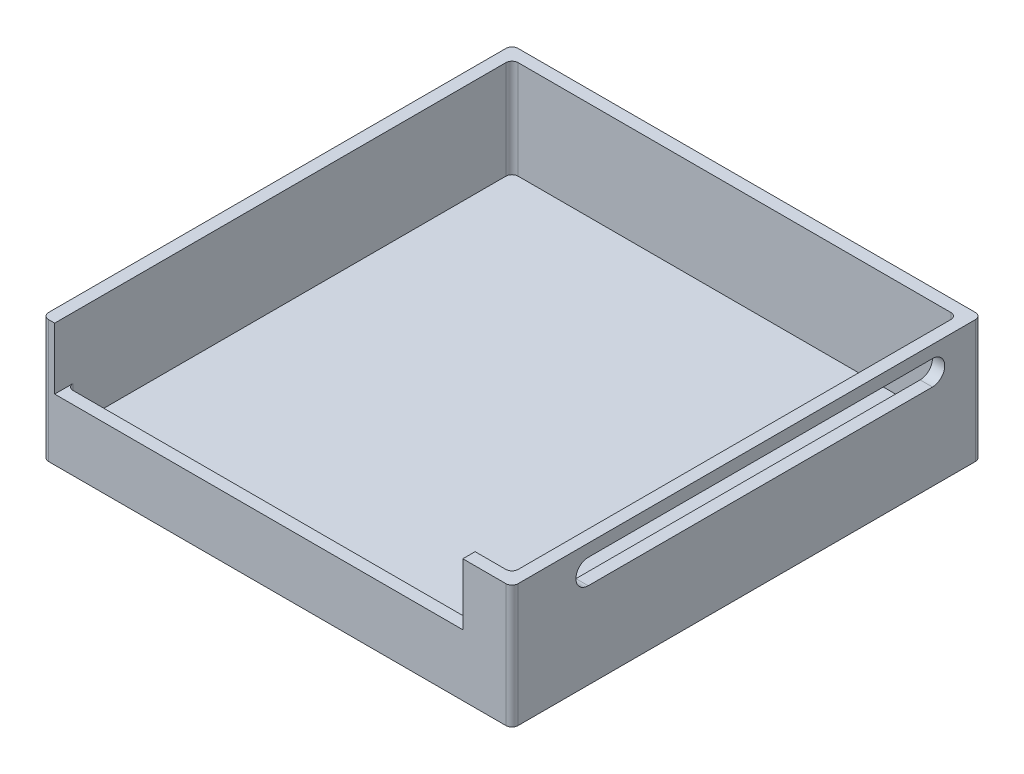
SolidWorks part; units mm, degrees
ref_plane "Front Plane" through (0, 0, 0) normal (0, 0, 1) x (1, 0, 0)
ref_plane "Top Plane" through (0, 0, 0) normal (0, 1, 0) x (1, 0, 0)
ref_plane "Right Plane" through (0, 0, 0) normal (1, 0, 0) x (0, 0, -1)
sketch "Sketch1" plane through (0, 0, 0) normal (0, 1, 0) x (1, 0, 0)
  line L1 (-88, 90.5) -> (88, 90.5)
  line L2 (-90.5, 88) -> (-90.5, -88)
  line L3 (-88, -90.5) -> (88, -90.5)
  line L4 (90.5, 88) -> (90.5, -88)
  line L5 (-90.5, 90.5) -> (90.5, -90.5) construction
  line L6 (-90.5, -90.5) -> (90.5, 90.5) construction
  line L7 (-93, 95.5) -> (93, 95.5)
  line L8 (-95.5, 93) -> (-95.5, -93)
  line L9 (-93, -95.5) -> (93, -95.5)
  line L10 (95.5, 93) -> (95.5, -93)
  line L11 (-95.5, 95.5) -> (95.5, -95.5) construction
  line L12 (-95.5, -95.5) -> (95.5, 95.5) construction
  arc A0 (90.5, 88) -> (88, 90.5) centre (88, 88) ccw
  arc A1 (-88, 90.5) -> (-90.5, 88) centre (-88, 88) ccw
  arc A2 (-90.5, -88) -> (-88, -90.5) centre (-88, -88) ccw
  arc A3 (88, -90.5) -> (90.5, -88) centre (88, -88) ccw
  arc A4 (-95.5, 93) -> (-93, 95.5) centre (-93, 93) cw
  arc A5 (-93, -95.5) -> (-95.5, -93) centre (-93, -93) cw
  arc A6 (93, -95.5) -> (95.5, -93) centre (93, -93) ccw
  arc A7 (95.5, 93) -> (93, 95.5) centre (93, 93) ccw
  point P0 (0, 0)
  point P18 (0, 0)
  dimension "D2" = 2.5
  dimension "D5" = 2.5
  dimension "D1" = 181
  dimension "18.1" = 181
  dimension "D3" = 191
  dimension "D4" = 191
extrude "Boss-Extrude2" add sketch "Sketch1" along normal blind 50
sketch "Sketch2" plane through (0, 0, 0) normal (0, 1, 0) x (1, 0, 0)
  line L1 (-88, 90.5) -> (88, 90.5)
  line L2 (-90.5, 88) -> (-90.5, -88)
  line L3 (-88, -90.5) -> (88, -90.5)
  line L4 (90.5, 88) -> (90.5, -88)
  line L5 (-90.5, 90.5) -> (90.5, -90.5) construction
  line L6 (-90.5, -90.5) -> (90.5, 90.5) construction
  arc A0 (-88, 90.5) -> (-90.5, 88) centre (-88, 88) ccw
  arc A1 (-90.5, -88) -> (-88, -90.5) centre (-88, -88) ccw
  arc A2 (88, -90.5) -> (90.5, -88) centre (88, -88) ccw
  arc A3 (90.5, 88) -> (88, 90.5) centre (88, 88) ccw
  point P1 (0, 0)
  dimension "D3" = 2.5
  dimension "D1" = 181
  dimension "D2" = 181
extrude "Boss-Extrude3" add sketch "Sketch2" along normal blind 10
sketch "Sketch3" plane through (0, 0, 95.5) normal (0, 0, 1) x (1, 0, 0)
  line L0 (0, 0) -> (0, 25)
  line L1 (-93, 0) -> (93, 0) construction
  line L2 (0, 25) -> (-93, 25)
  line L3 (75.5, 25) -> (75.5, 50)
  line L4 (-93, 50) -> (-93, 0) construction
  line L5 (-90.5, 25) -> (-90.5, 50)
  line L6 (93, 50) -> (93, 0) construction
  line L7 (-90.5, 25) -> (75.5, 25)
  line L8 (75.5, 50) -> (75.5, 25)
  line L9 (-93, 50) -> (93, 50) construction
  line L10 (-90.5, 50) -> (-90.5, 25)
  line L11 (-90.5, 50) -> (75.5, 50)
  line L12 (75.5, 50) -> (-90.5, 50)
  line M8 (93, 50) -> (-93, 50)
  dimension "D1" = 25
  dimension "D2" = 17.5
  dimension "D3" = 2.5
extrude "Cut-Extrude1" cut sketch "Sketch3" against normal blind 10 contours L2 L7 L3 L5 M8
sketch "Sketch4" plane through (95.5, 0, 0) normal (1, 0, 0) x (0, 0, -1)
  line L0 (-64.5, 50) -> (-64.5, 10)
  line L1 (-93, 50) -> (93, 50) construction
  line L2 (-64.5, 35) -> (75.5, 35)
  line L3 (75.5, 35) -> (75.5, 45)
  line L4 (75.5, 45) -> (-64.5, 45)
  line L5 (-64.5, 45) -> (-64.5, 35)
  line L6 (93, 50) -> (93, 0) construction
  arc A0 (75.5, 35) -> (75.5, 45) centre (75.5, 40) ccw
  arc A1 (-64.5, 45) -> (-64.5, 35) centre (-64.5, 40) ccw
  dimension "D1" = 40
  dimension "D2" = 140
  dimension "D3" = 17.5
  dimension "D4" = 17.5
  dimension "D5" = 10
  dimension "D6" = 5
extrude "Cut-Extrude2" cut sketch "Sketch4" against normal blind 10 contours L3 L4 L0 L2 | L3 A0 | L0 A1
